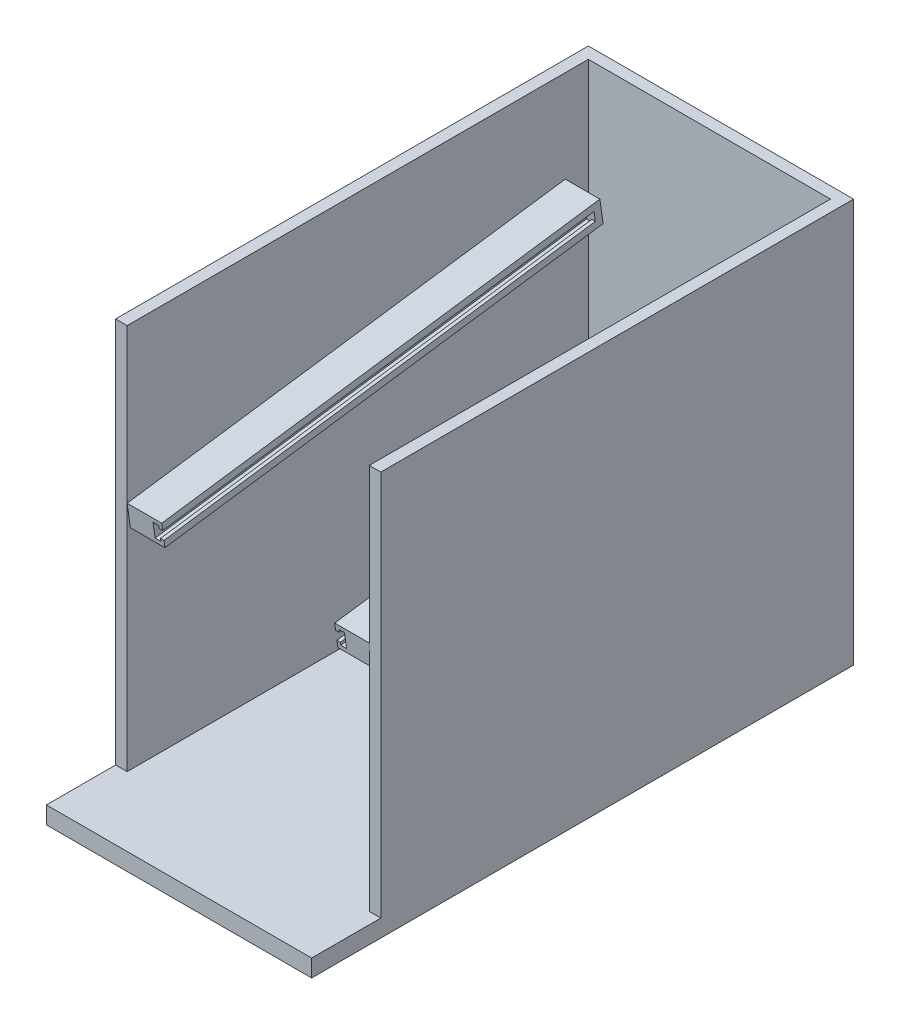
SolidWorks part; units mm, degrees
ref_plane "Front Plane" through (0, 0, 0) normal (0, 0, 1) x (1, 0, 0)
ref_plane "Top Plane" through (0, 0, 0) normal (0, 1, 0) x (1, 0, 0)
ref_plane "Right Plane" through (0, 0, 0) normal (1, 0, 0) x (0, 0, -1)
sketch "Sketch1" plane through (0, 0, 0) normal (0, 1, 0) x (1, 0, 0)
  line L1 (-146.05, -298.45) -> (146.05, -298.45)
  line L2 (-146.05, -298.45) -> (-146.05, 298.45)
  line L3 (-146.05, 298.45) -> (146.05, 298.45)
  line L4 (146.05, -298.45) -> (146.05, 298.45)
  line L5 (-146.05, -298.45) -> (146.05, 298.45) construction
  line L6 (-146.05, 298.45) -> (146.05, -298.45) construction
  point P0 (0, 0)
  dimension "D1" = 596.9
  dimension "D2" = 292.1
extrude "Boss-Extrude1" add sketch "Sketch1" along normal blind 19.05
sketch "Sketch2" plane through (0, 19.05, 0) normal (0, 1, 0) x (1, 0, 0)
  line L0 (-146.05, -222.25) -> (-146.05, 298.45)
  line L1 (-146.05, 298.45) -> (-146.05, -298.45) construction
  line L2 (-146.05, 298.45) -> (146.05, 298.45)
  line L3 (146.05, 298.45) -> (-146.05, 298.45) construction
  line L4 (146.05, -298.45) -> (146.05, 298.45) construction
  line L5 (146.05, 298.45) -> (146.05, -222.25)
  line L6 (146.05, -222.25) -> (133.35, -222.25)
  line L7 (133.35, -222.25) -> (133.35, 285.75)
  line L8 (133.35, 285.75) -> (-133.35, 285.75)
  line L9 (-133.35, 285.75) -> (-133.35, -222.25)
  line L10 (-133.35, -222.25) -> (-146.05, -222.25)
  dimension "D1" = 76.2
  dimension "D2" = 12.7
  dimension "D3" = 12.7
extrude "Boss-Extrude2" add sketch "Sketch2" along normal blind 425.45
sketch "Sketch3" plane through (-133.35, 0, 0) normal (1, 0, 0) x (0, 0, -1)
  line L0 (-222.25, 275.075) -> (260.35, 342.9)
  line L1 (285.75, 444.5) -> (285.75, 19.05) construction
  line L2 (263.885, 317.7472) -> (-218.715, 249.9222)
  line L3 (-218.715, 249.9222) -> (-222.25, 275.075)
  line L4 (260.35, 342.9) -> (263.885, 317.7472)
  line L5 (-222.25, 19.05) -> (285.75, 19.05) construction
  line L6 (-222.25, 444.5) -> (-222.25, 19.05) construction
  line L7 (-222.25, 444.5) -> (285.75, 444.5) construction
  dimension "D1" = 25.4
  dimension "D2" = 8
  dimension "D3" = 25.4
  dimension "D4" = 101.6
extrude "Boss-Extrude3" add sketch "Sketch3" along normal blind 38.1
sketch "Sketch4" plane through (-95.25, 0, 0) normal (1, 0, 0) x (0, 0, -1)
  line L0 (-221.1964, 267.5786) -> (-219.7686, 257.4186)
  line L1 (-222.25, 275.075) -> (-218.715, 249.9222) construction
  line L2 (-219.7686, 257.4186) -> (255.2856, 324.1831)
  line L4 (255.2856, 324.1831) -> (253.8577, 334.3431)
  line L5 (253.8577, 334.3431) -> (-221.1964, 267.5786)
  line L8 (-219.7686, 257.4186) -> (-218.715, 249.9222) construction
  line L9 (-221.1964, 267.5786) -> (-222.25, 275.075) construction
  dimension "D1" = 10.16
  dimension "D2" = 7.62
extrude "Cut-Extrude1" cut sketch "Sketch4" against normal blind 10.16 contours L5 L0 L2 L4
sketch "Sketch5" plane through (0, 292.8808, 41.1617) normal (0, -0.9903, -0.1392) x (1, 0, 0)
  line L0 (-105.41, 181.804) -> (-95.25, 181.804) construction
  line L1 (-99.06, 181.804) -> (-105.41, 181.804)
  line L2 (-99.06, 181.804) -> (-99.06, -297.9187)
  line L3 (-99.06, -297.9187) -> (-105.41, -297.9187)
  line L4 (-105.41, 181.804) -> (-105.41, -297.9187)
  line L5 (-105.41, -297.9187) -> (-95.25, -297.9187) construction
  line L6 (-105.41, -297.9187) -> (-105.41, 181.804) construction
  dimension "D1" = 3.81
extrude "Cut-Extrude2" cut sketch "Sketch5" against normal blind 3.175 and the other way blind 13.335 contours L2 L3 L4 L1
mirror "Mirror1" about plane through (0, 0, 0) normal (1, 0, 0) of "Cut-Extrude2", "Cut-Extrude1", "Boss-Extrude3"
sketch "Sketch6" plane through (0, 19.05, 0) normal (0, 1, 0) x (1, 0, 0)
  line L0 (-133.35, 285.75) -> (133.35, 285.75) construction
  line L1 (-12.7, 285.75) -> (12.7, 285.75)
  line L2 (-12.7, 285.75) -> (-12.7, 107.95)
  line L3 (-12.7, 107.95) -> (12.7, 107.95)
  line L4 (12.7, 285.75) -> (12.7, 107.95)
  point P7 (0, 107.95)
  dimension "D1" = 177.8
  dimension "D2" = 25.4
extrude "Boss-Extrude4" add sketch "Sketch6" along normal blind 241.3
sketch "Sketch8" plane through (0, 0, -285.75) normal (0, 0, 1) x (1, 0, 0)
  line L1 (-123.19, 19.05) -> (-41.91, 19.05)
  line L2 (-133.35, 29.21) -> (-133.35, 148.59)
  line L3 (-123.19, 158.75) -> (-41.91, 158.75)
  line L4 (-31.75, 29.21) -> (-31.75, 148.59)
  arc A0 (-41.91, 19.05) -> (-31.75, 29.21) centre (-41.91, 29.21) ccw
  arc A1 (-123.19, 19.05) -> (-133.35, 29.21) centre (-123.19, 29.21) cw
  arc A2 (-133.35, 148.59) -> (-123.19, 158.75) centre (-123.19, 148.59) cw
  arc A3 (-41.91, 158.75) -> (-31.75, 148.59) centre (-41.91, 148.59) cw
  point P7 (-31.75, 19.05)
  point P10 (-133.35, 19.05)
  point P13 (-133.35, 158.75)
  point P16 (-31.75, 158.75)
  dimension "D3" = 10.16
  dimension "D1" = 101.6
  dimension "D2" = 139.7
extrude "Boss-Extrude6" add sketch "Sketch8" along normal blind 38.1
sketch "Sketch9" plane through (0, 0, -247.65) normal (0, 0, 1) x (1, 0, 0)
  line L0 (-41.91, 158.75) -> (-123.19, 158.75) construction
  line L1 (-118.11, 139.7) -> (-46.99, 139.7)
  line L2 (-120.65, 137.16) -> (-120.65, 66.04)
  line L3 (-118.11, 63.5) -> (-46.99, 63.5)
  line L4 (-44.45, 137.16) -> (-44.45, 66.04)
  line L5 (-123.19, 19.05) -> (-41.91, 19.05) construction
  arc A0 (-120.65, 66.04) -> (-118.11, 63.5) centre (-118.11, 66.04) ccw
  arc A1 (-46.99, 63.5) -> (-44.45, 66.04) centre (-46.99, 66.04) ccw
  arc A2 (-46.99, 139.7) -> (-44.45, 137.16) centre (-46.99, 137.16) cw
  arc A3 (-118.11, 139.7) -> (-120.65, 137.16) centre (-118.11, 137.16) ccw
  point P10 (-82.55, 139.7)
  point P11 (-82.55, 158.75)
  dimension "D3" = 2.54
  dimension "D1" = 19.05
  dimension "D2" = 44.45
extrude "Cut-Extrude3" cut sketch "Sketch9" against normal blind 3.81
